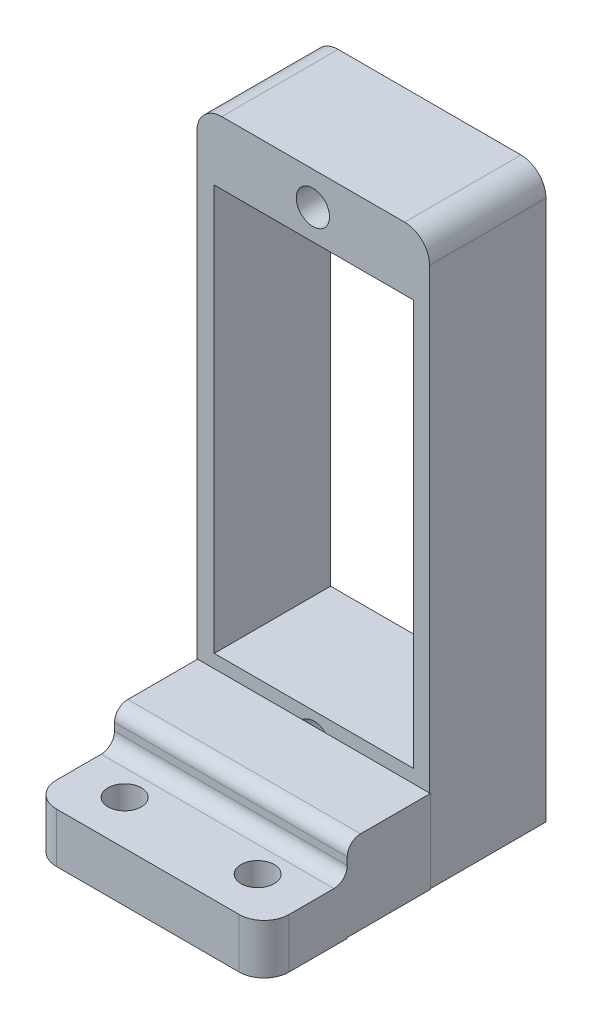
SolidWorks part; units mm, degrees
ref_plane "Front Plane" through (0, 0, 0) normal (0, 0, 1) x (1, 0, 0)
ref_plane "Top Plane" through (0, 0, 0) normal (0, 1, 0) x (1, 0, 0)
ref_plane "Right Plane" through (0, 0, 0) normal (1, 0, 0) x (0, 0, -1)
other "Graphic1"
other "object_1 (Open) -1"
ref_plane "Plane1" through (0, 0, 25) normal (0, 0, 1) x (1, 0, 0)
sketch "Sketch1" plane through (0, 0, 25) normal (0, 0, 1) x (1, 0, 0)
  line L1 (231.953, 496.9906) -> (245.953, 496.9906)
  line L2 (231.953, 496.9906) -> (231.953, 462.9906)
  line L3 (231.953, 462.9906) -> (245.953, 462.9906)
  line L4 (245.953, 496.9906) -> (245.953, 462.9906)
  point P4 (231.953, 496.9906)
  point P6 (0, 0)
  dimension "D1" = 14
  dimension "D2" = 34
extrude "Boss-Extrude1" add sketch "Sketch1" along normal blind 7
sketch "Sketch2" plane through (0, 0, 32) normal (0, 0, 1) x (1, 0, 0)
  line L1 (233, 493.2) -> (245, 493.2)
  line L2 (233, 493.2) -> (233, 468.8)
  line L3 (233, 468.8) -> (245, 468.8)
  line L4 (245, 493.2) -> (245, 468.8)
  circle A0 centre (238.9351, 495.0031) radius 1
  dimension "D1" = 12
  dimension "D2" = 24.4
extrude "Cut-Extrude1" cut sketch "Sketch2" against normal through all
sketch "Sketch3" plane through (0, 0, 32) normal (0, 0, 1) x (1, 0, 0)
  line L1 (232, 468) -> (246, 468)
  line L2 (232, 468) -> (232, 463)
  line L3 (232, 463) -> (246, 463)
  line L4 (246, 468) -> (246, 463)
  dimension "D1" = 14
  dimension "D2" = 5
extrude "Boss-Extrude2" add sketch "Sketch3" along normal blind 5
sketch "Sketch4" plane through (0, 0, 37) normal (0, 0, 1) x (1, 0, 0)
  line L1 (232, 465.9467) -> (246, 465.9467)
  line L2 (232, 465.9467) -> (232, 462.9467)
  line L3 (232, 462.9467) -> (246, 462.9467)
  line L4 (246, 465.9467) -> (246, 462.9467)
  dimension "D1" = 14
  dimension "D2" = 3
extrude "Boss-Extrude3" add sketch "Sketch4" along normal blind 5
fillet "Fillet1" radius 1.5 4 edges at (232, 464.4467, 42) (246, 464.4467, 42) (231.953, 496.9906, 28.5) (245.953, 496.9906, 28.5)
fillet "Fillet2" radius 0.8 2 edges at (239, 465.9467, 37) (239, 468, 37)
sketch "Sketch5" plane through (0, 0, 25) normal (0, 0, -1) x (-1, 0, 0)
  line L0 (-238.9964, 468.8) -> (-238.9964, 461.5771) construction
  circle A0 centre (-238.9964, 467.2725) radius 1
  point P2 (-238.9964, 467.2725)
extrude "Cut-Extrude2" cut sketch "Sketch5" against normal blind 7
sketch "Sketch6" plane through (0, 465.9467, 0) normal (0, 1, 0) x (1, 0, 0)
  circle A0 centre (234.9515, -39.3412) radius 1
  circle A1 centre (242.9515, -39.3412) radius 1
  dimension "D1" = 8
extrude "Cut-Extrude3" cut sketch "Sketch6" against normal through all
